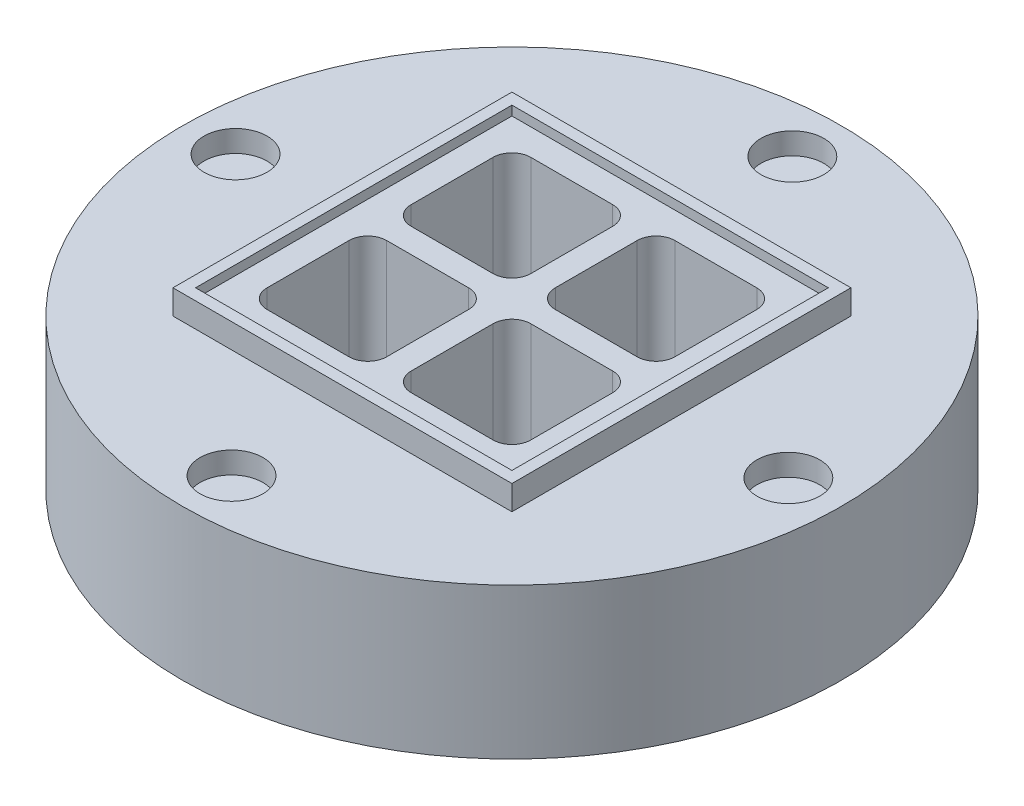
SolidWorks part; units mm, degrees
material "ABS"
ref_plane "Front Plane" through (0, 0, 0) normal (0, 0, 1) x (1, 0, 0)
ref_plane "Top Plane" through (0, 0, 0) normal (0, 1, 0) x (1, 0, 0)
ref_plane "Right Plane" through (0, 0, 0) normal (1, 0, 0) x (0, 0, -1)
sketch "Sketch1" plane through (0, 0, 0) normal (0, 1, 0) x (1, 0, 0)
  circle A0 centre (0, 0) radius 17.5
  dimension "D1" = 35
extrude "Boss-Extrude1" add sketch "Sketch1" along normal blind 8
sketch "Sketch5" plane through (0, 0, 0) normal (0, -1, 0) x (1, 0, 0)
  circle A2 centre (0, 0) radius 16.5
  circle A3 centre (0, 0) radius 16.5
  dimension "D1" = 1
extrude "Cut-Extrude2" cut sketch "Sketch5" against normal blind 1
sketch "Sketch11" plane through (0, 8, 0) normal (0, 1, 0) x (1, 0, 0)
  line L0 (0, 17.5) -> (0, 16.45) construction
  circle A0 centre (0, 0) radius 17.5 construction
  circle A1 centre (0.1067, 14.7834) radius 1.67
  dimension "D2" = 3.34
  dimension "D1" = 1.05
extrude "Cut-Extrude5" cut sketch "Sketch11" against normal blind 1.15
pattern_circular "CirPattern1" count 4 over 360 about axis through (0, 0, 0) along (0, 1, 0) of "Cut-Extrude5"
sketch "Sketch13" plane through (0, 8, 0) normal (0, 1, 0) x (1, 0, 0)
  line L1 (9, -9) -> (-9, -9)
  line L2 (9, -9) -> (9, 9)
  line L3 (9, 9) -> (-9, 9)
  line L4 (-9, -9) -> (-9, 9)
  line L5 (9, -9) -> (-9, 9) construction
  line L6 (9, 9) -> (-9, -9) construction
  line L7 (8.4, -8.4) -> (-8.4, -8.4)
  line L8 (8.4, -8.4) -> (8.4, 8.4)
  line L9 (8.4, 8.4) -> (-8.4, 8.4)
  line L10 (-8.4, -8.4) -> (-8.4, 8.4)
  line L11 (8.4, -8.4) -> (-8.4, 8.4) construction
  line L12 (8.4, 8.4) -> (-8.4, -8.4) construction
  point P0 (0, 0)
  point P7 (0, 0)
  point P28 (0, 0)
  dimension "D1" = 18
  dimension "D3" = 16.8
extrude "Boss-Extrude3" add sketch "Sketch13" along normal blind 1.3 contours L4 L1 L2 L3 L7 L10 L9 L8
sketch "Sketch12" plane through (0, 8, 0) normal (0, 1, 0) x (1, 0, 0)
  line L1 (-9, -9) -> (9, 9) construction
  line L2 (-9, -9) -> (9, -9)
  line L3 (-9, -9) -> (-9, 9)
  line L4 (-9, 9) -> (9, 9)
  line L5 (9, -9) -> (9, 9)
  line L6 (9, -9) -> (-9, 9) construction
  line L7 (-7, 7) -> (7, 7)
  line L8 (-7, 7) -> (-7, -7)
  line L9 (-7, -7) -> (7, -7)
  line L10 (7, 7) -> (7, -7)
  line L11 (-7, 7) -> (7, -7) construction
  line L12 (-7, -7) -> (7, 7) construction
  line L13 (-0.6509, 7) -> (0.6509, 7)
  line L14 (-0.6509, 7) -> (-0.6509, -7)
  line L15 (-0.6509, -7) -> (0.6509, -7)
  line L16 (0.6509, 7) -> (0.6509, -7)
  line L17 (-0.6509, 7) -> (0.6509, -7) construction
  line L18 (-0.6509, -7) -> (0.6509, 7) construction
  line L19 (-7, 0.6509) -> (7, 0.6509)
  line L20 (-7, 0.6509) -> (-7, -0.6509)
  line L21 (-7, -0.6509) -> (7, -0.6509)
  line L22 (7, 0.6509) -> (7, -0.6509)
  line L23 (-7, 0.6509) -> (7, -0.6509) construction
  line L24 (-7, -0.6509) -> (7, 0.6509) construction
  point P0 (0, 0)
  point P5 (-0.1056, 0.0854)
  point P7 (0, 0)
  point P16 (0, 0)
  point P21 (0, 0)
  point P26 (-0.1056, 0.0854)
  line M11 (9, -9) -> (-9, -9)
  line M12 (-9, -9) -> (-9, 9)
  line M13 (-9, 9) -> (9, 9)
  line M14 (9, 9) -> (9, -9)
  dimension "D1" = 14
extrude "Boss-Extrude2" add sketch "Sketch12" along normal blind 0.8 contours L7 L10 L9 L8 M12 M11 M14 M13 | L8 L21 L14 L19 | L14 L19 L16 L7 | L21 L14 L9 L16 | L14 L21 L16 L19 | L16 L21 L10 L19
sketch "Sketch14" plane through (0, 8, 0) normal (0, 1, 0) x (1, 0, 0)
  line L1 (-7, 7) -> (-0.6509, 7)
  line L2 (-7, 7) -> (-7, 0.6509)
  line L3 (-7, 0.6509) -> (-0.6509, 0.6509)
  line L4 (-0.6509, 7) -> (-0.6509, 0.6509)
  line L5 (-0.6509, -0.6509) -> (-7, -0.6509)
  line L6 (-0.6509, -0.6509) -> (-0.6509, -7)
  line L7 (-0.6509, -7) -> (-7, -7)
  line L8 (-7, -0.6509) -> (-7, -7)
  line L9 (0.6509, -7) -> (7, -7)
  line L10 (0.6509, -7) -> (0.6509, -0.6509)
  line L11 (0.6509, -0.6509) -> (7, -0.6509)
  line L12 (7, -7) -> (7, -0.6509)
  line L13 (7, 0.6509) -> (0.6509, 0.6509)
  line L14 (7, 0.6509) -> (7, 7)
  line L15 (7, 7) -> (0.6509, 7)
  line L16 (0.6509, 0.6509) -> (0.6509, 7)
extrude "Cut-Extrude6" cut sketch "Sketch14" against normal through all
fillet "Fillet1" radius 1 16 edges at (-7, 4.9, 0.6509) (-0.6509, 4.9, 0.6509) (-0.6509, 4.9, 7) (-0.6509, 4.9, -7) (-0.6509, 4.9, -0.6509) (-7, 4.9, -0.6509) (0.6509, 4.9, 7) (0.6509, 4.9, 0.6509) (7, 4.9, 0.6509) (7, 4.9, -0.6509) (0.6509, 4.9, -0.6509) (0.6509, 4.9, -7) (-7, 4.9, -7) (7, 4.9, 7) (7, 4.9, -7) (-7, 4.9, 7)
